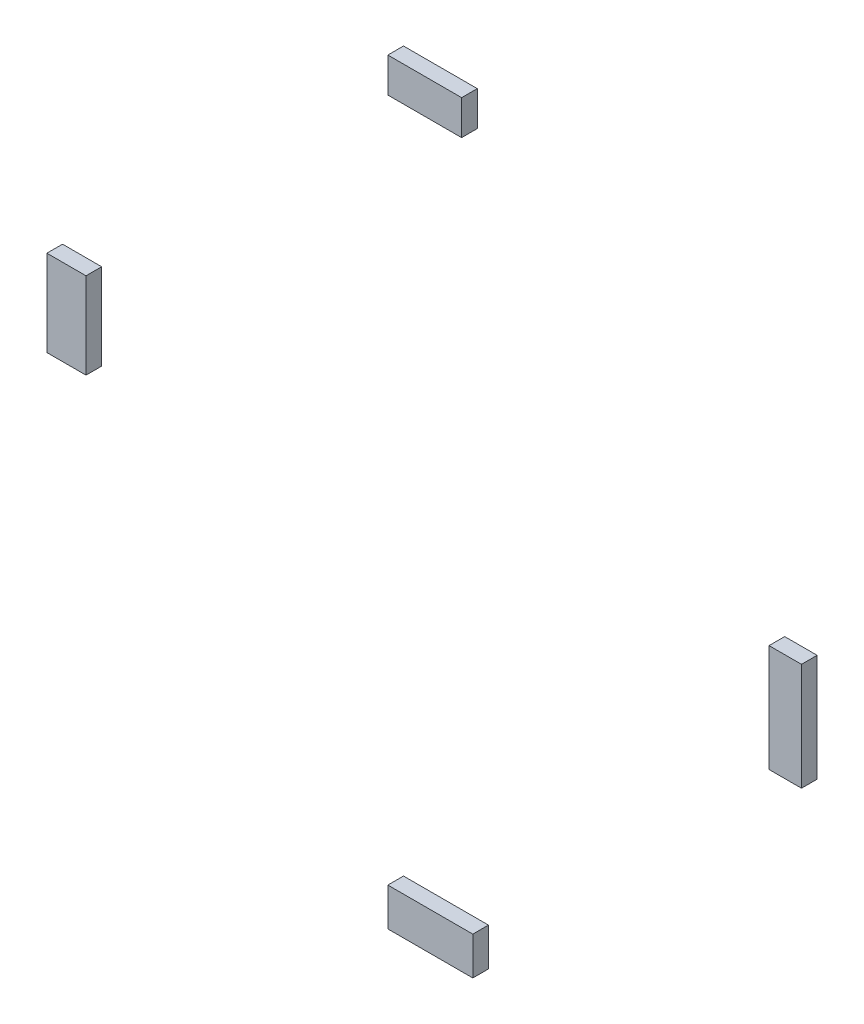
SolidWorks part; units mm, degrees
ref_plane "Plan de face" through (0, 0, 0) normal (0, 0, 1) x (1, 0, 0)
ref_plane "Plan de dessus" through (0, 0, 0) normal (0, 1, 0) x (1, 0, 0)
ref_plane "Plan de droite" through (0, 0, 0) normal (1, 0, 0) x (0, 0, -1)
other "Graphique1"
other "Graphique (Fermé) -1"
sketch "Esquisse2" plane through (0, 0, 0) normal (0, 0, 1) x (1, 0, 0)
  line L1 (-7.1735, 72.66) -> (6.9713, 72.66)
  line L2 (-7.1735, 72.66) -> (-7.1735, 66.0162)
  line L3 (-7.1735, 66.0162) -> (6.9713, 66.0162)
  line L4 (6.9713, 72.66) -> (6.9713, 66.0162)
  line L5 (-72.5398, 7.0794) -> (-65.0388, 7.0794)
  line L6 (-72.5398, 7.0794) -> (-72.5398, -9.4229)
  line L7 (-72.5398, -9.4229) -> (-65.0388, -9.4229)
  line L8 (-65.0388, 7.0794) -> (-65.0388, -9.4229)
  line L9 (65.9081, 11.1514) -> (72.1233, 11.1514)
  line L10 (65.9081, 11.1514) -> (65.9081, -9.4229)
  line L11 (65.9081, -9.4229) -> (72.1233, -9.4229)
  line L12 (72.1233, 11.1514) -> (72.1233, -9.4229)
  line L13 (-7.1735, -65.145) -> (9.1145, -65.145)
  line L14 (-7.1735, -65.145) -> (-7.1735, -72.4317)
  line L15 (-7.1735, -72.4317) -> (9.1145, -72.4317)
  line L16 (9.1145, -65.145) -> (9.1145, -72.4317)
extrude "Boss.-Extru.1" add sketch "Esquisse2" along normal blind 3
sketch "Esquisse4" plane through (0, 0, 0) normal (0, 0, 1) x (1, 0, 0)
  line L0 (-48.3221, 56.372) -> (0, 0) construction
  line L1 (0, 0) -> (-24.8549, -70.5918) construction
  line L2 (-24.8549, -70.5918) -> (0, 0) construction
  line L3 (0, 0) -> (73.691, 13.7951) construction
  circle A0 centre (-44.9063, 52.3872) radius 1
  circle A1 centre (67.8218, 12.6964) radius 1
  circle A2 centre (-22.9155, -65.0836) radius 1
  point P13 (-25.819, 61.7299)
  point P14 (-150.3364, 78.4466)
  dimension "D5" = 69
  dimension "D6" = 2
  dimension "D7" = 2
  dimension "D8" = 2
  dimension "D1" = 120
  dimension "D2" = 120
  dimension "D3" = 69
  dimension "D4" = 69
